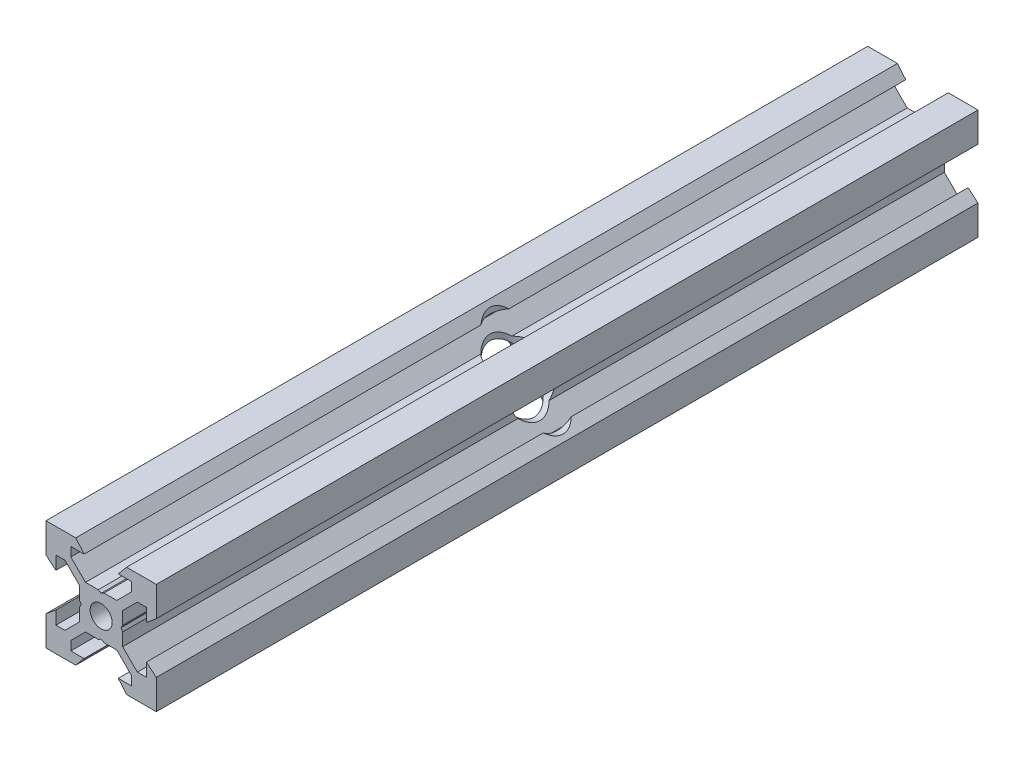
SolidWorks part; units mm, degrees
material "3.3535 (EN-AW 5754)"
ref_plane "Front Plane" through (0, 0, 0) normal (0, 0, 1) x (1, 0, 0)
ref_plane "Top Plane" through (0, 0, 0) normal (0, 1, 0) x (1, 0, 0)
ref_plane "Right Plane" through (0, 0, 0) normal (1, 0, 0) x (0, 0, -1)
sketch "Sketch1" plane through (0, 0, 0) normal (0, 0, 1) x (1, 0, 0)
  line L0 (10, 10) -> (4.6104, 10) construction
  line L1 (10, 10) -> (10, 4.6104) construction
  line L2 (10, -10) -> (10, -4.6104) construction
  line L3 (10, -10) -> (4.6104, -10) construction
  line L4 (10, 10) -> (10, 4.6104)
  line L5 (6.5607, 5.5) -> (8.2, 5.5)
  line L6 (5.5, 8.2) -> (5.5, 6.5607)
  line L7 (10, 10) -> (4.6104, 10)
  line L8 (10, 10) -> (10, 4.6104)
  line L9 (6.5607, 5.5) -> (3.9, 2.8393)
  line L10 (5.5, 6.5607) -> (2.8393, 3.9)
  line L11 (10, 4.6104) -> (8.2, 3.1)
  line L12 (4.6104, 10) -> (3.1, 8.2)
  line L13 (8.2, 3.1) -> (8.2, 5.5)
  line L14 (3.1, 8.2) -> (5.5, 8.2)
  line L15 (-6.5607, 5.5) -> (-8.2, 5.5)
  line L16 (6.5607, -5.5) -> (8.2, -5.5)
  line L17 (3.1, -8.2) -> (5.5, -8.2)
  line L18 (8.2, -3.1) -> (8.2, -5.5)
  line L19 (4.6104, -10) -> (3.1, -8.2)
  line L20 (10, -4.6104) -> (8.2, -3.1)
  line L21 (0.5196, -3.9) -> (0, -3.6)
  line L22 (0.5196, 3.9) -> (0, 3.6)
  line L23 (3.6, 0) -> (3.9, -0.5196)
  line L24 (3.9, 0.5196) -> (3.6, 0)
  line L25 (3.9, 0.5196) -> (3.9, 2.8393)
  line L26 (2.8393, 3.9) -> (0.5196, 3.9)
  line L27 (3.9, -2.8393) -> (3.9, -0.5196)
  line L28 (2.8393, -3.9) -> (0.5196, -3.9)
  line L29 (5.5, -6.5607) -> (2.8393, -3.9)
  line L30 (6.5607, -5.5) -> (3.9, -2.8393)
  line L31 (10, -10) -> (10, -4.6104)
  line L32 (10, -10) -> (4.6104, -10)
  line L33 (5.5, -8.2) -> (5.5, -6.5607)
  line L34 (-6.5607, -5.5) -> (-8.2, -5.5)
  line L35 (10, -10) -> (10, -4.6104)
  line L36 (0, 0) -> (0, 8.2) construction
  line L37 (-10, -10) -> (-4.6104, -10) construction
  line L38 (-10, -10) -> (-10, -4.6104) construction
  line L39 (-10, 10) -> (-10, 4.6104) construction
  line L40 (-10, 10) -> (-4.6104, 10) construction
  line L41 (-10, -10) -> (-10, -4.6104)
  line L43 (-5.5, -8.2) -> (-5.5, -6.5607)
  line L44 (-10, -10) -> (-4.6104, -10)
  line L45 (-10, -10) -> (-10, -4.6104)
  line L46 (-6.5607, -5.5) -> (-3.9, -2.8393)
  line L47 (-5.5, -6.5607) -> (-2.8393, -3.9)
  line L48 (-2.8393, -3.9) -> (-0.5196, -3.9)
  line L49 (-3.9, -2.8393) -> (-3.9, -0.5196)
  line L50 (-2.8393, 3.9) -> (-0.5196, 3.9)
  line L51 (-3.9, 0.5196) -> (-3.9, 2.8393)
  line L52 (-3.9, 0.5196) -> (-3.6, 0)
  line L53 (-3.6, 0) -> (-3.9, -0.5196)
  line L54 (-0.5196, 3.9) -> (0, 3.6)
  line L55 (-0.5196, -3.9) -> (0, -3.6)
  line L56 (-10, -4.6104) -> (-8.2, -3.1)
  line L57 (-4.6104, -10) -> (-3.1, -8.2)
  line L58 (-8.2, -3.1) -> (-8.2, -5.5)
  line L59 (-3.1, -8.2) -> (-5.5, -8.2)
  line L60 (-10, -10) -> (10, -10) construction
  line L61 (-10, -10) -> (-10, 10) construction
  line L62 (-3.1, 8.2) -> (-5.5, 8.2)
  line L63 (-8.2, 3.1) -> (-8.2, 5.5)
  line L64 (-4.6104, 10) -> (-3.1, 8.2)
  line L65 (-10, 4.6104) -> (-8.2, 3.1)
  line L66 (-5.5, 6.5607) -> (-2.8393, 3.9)
  line L67 (-6.5607, 5.5) -> (-3.9, 2.8393)
  line L68 (-10, 10) -> (-10, 4.6104)
  line L69 (-10, 10) -> (-4.6104, 10)
  line L70 (-5.5, 8.2) -> (-5.5, 6.5607)
  line L71 (-10, 10) -> (10, 10) construction
  line L72 (-10, 10) -> (-10, 4.6104)
  line L73 (10, -10) -> (10, 10) construction
  line L74 (-10, -10) -> (10, 10) construction
  line L75 (-10, 10) -> (10, -10) construction
  circle A0 centre (0, 0) radius 2
  dimension "D7" = 4
  dimension "D1" = 20
  dimension "D2" = 5.3896
  dimension "D3" = 4.5
  dimension "D4" = 50
  dimension "D5" = 1.8
  dimension "D6" = 1.5104
  dimension "D8" = 5.5
  dimension "D9" = 120
  dimension "D10" = 0.3
  dimension "D11" = 2.3197
  dimension "D12" = 7.8
  dimension "D13" = 7.8
  dimension "D14" = 1.5
  dimension "D15" = 2.6607
extrude "Boss-Extrude1" add sketch "Sketch1" along normal blind 149 contours L70 L62 L64 L69 L68 L65 L63 L15 L67 L51 L52 L53 L49 L46 L34 L58 L56 L41 L44 L57 L59 L43 L47 L48 L55 L21 L28 L29 L33 L17 L19 L32 L31 L20 L18 L16 L30 L27 L23 L24 L25 L9 L5 L13 L11 L4 L7 L12 L14 L6 L10
sketch "Sketch4" plane through (0, 0, 0) normal (1, 0, 0) x (0, 0, -1)
  line L0 (-149, 0) -> (0, 0) construction
  circle A0 centre (-74.5, 0) radius 4
  dimension "D1" = 8
extrude "Cut-Extrude1" cut sketch "Sketch4" against normal through all both and the other way through all
sketch "Sketch5" plane through (0, 0, 0) normal (0, 1, 0) x (1, 0, 0)
  line L0 (0, 0) -> (0, -149) construction
  circle A0 centre (0, -74.5) radius 4
  dimension "D1" = 8
extrude "Cut-Extrude2" cut sketch "Sketch5" against normal through all both and the other way through all
